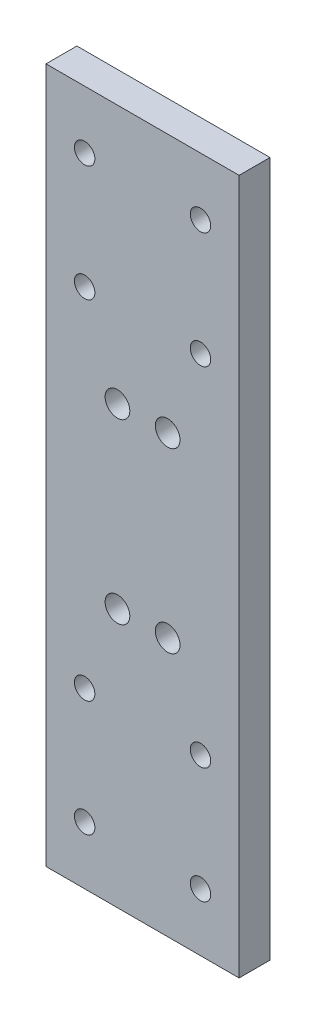
SolidWorks part; units mm, degrees
ref_plane "Front Plane" through (0, 0, 0) normal (0, 0, 1) x (1, 0, 0)
ref_plane "Top Plane" through (0, 0, 0) normal (0, 1, 0) x (1, 0, 0)
ref_plane "Right Plane" through (0, 0, 0) normal (1, 0, 0) x (0, 0, -1)
sketch "Sketch1" plane through (0, 0, 0) normal (0, 0, 1) x (1, 0, 0)
  line L0 (55, 0) -> (-55, 0) construction
  line L1 (-25, 90) -> (25, 90)
  line L2 (-25, 90) -> (-25, -90)
  line L3 (-25, -90) -> (25, -90)
  line L4 (25, 90) -> (25, -90)
  line L5 (0, -55) -> (0, 55) construction
  dimension "D1" = 50
  dimension "D2" = 180
  dimension "D3" = 90
  dimension "D4" = 25
extrude "Boss-Extrude1" add sketch "Sketch1" along normal blind 8
hole_wizard "M5 Clearance Hole1" positions "Sketch3" profile "Sketch2" hole size "M5" standard "ISO" end condition through all
sketch "Sketch3" plane through (0, 0, 8) normal (0, 0, 1) x (1, 0, 0)
  line L0 (55, 0) -> (-55, 0) construction
  line L1 (0, -55) -> (0, 55) construction
  line L2 (-74.3984, 0) -> (68.6052, 0) construction
  line L4 (0, 41.1376) -> (0, -28.8663) construction
  point P0 (-15, 45)
  point P23 (-15, -45)
  point P24 (15, -45)
  point P25 (15, 45)
  point P27 (-15, 75)
  point P31 (-15, -75)
  point P33 (15, -75)
  point P34 (15, 75)
  dimension "D1" = 45
  dimension "D2" = 15
  dimension "D3" = 15
  dimension "D4" = 30
sketch "Sketch2" plane through (-15, 45, 8) normal (1, 0, 0) x (0, -1, 0)
  line L0 (0, 0) -> (0, 8)
  line L1 (0, 8) -> (2.65, 8)
  line L2 (2.65, 8) -> (2.65, 0)
  line L5 (2.65, 0) -> (0, 0)
  line L11 (0, -6.35) -> (0, 107.95) construction
  dimension "Thru Hole Dia." = 5.3
  dimension "Thru Hole Depth" = 8
hole_wizard "M6 Clearance Hole1" positions "Sketch5" profile "Sketch4" hole size "M6" standard "ISO" end condition through all
sketch "Sketch5" plane through (0, 0, 8) normal (0, 0, 1) x (1, 0, 0)
  line L1 (55, 0) -> (-55, 0) construction
  line L2 (-63.4314, 0) -> (43.331, 0) construction
  line L3 (0, -55) -> (0, 55) construction
  line L4 (0, 43.8481) -> (0, -35.5104) construction
  point P0 (-6.5, 23)
  point P16 (-6.5, -23)
  point P26 (6.5, -23)
  point P27 (6.5, 23)
  dimension "D1" = 6.5
  dimension "D3" = 23
sketch "Sketch4" plane through (-6.5, 23, 8) normal (1, 0, 0) x (0, -1, 0)
  line L0 (0, 0) -> (0, 8)
  line L1 (0, 8) -> (3.2, 8)
  line L2 (3.2, 8) -> (3.2, 0)
  line L5 (3.2, 0) -> (0, 0)
  line L11 (0, -6.35) -> (0, 107.95) construction
  dimension "Thru Hole Dia." = 6.4
  dimension "Thru Hole Depth" = 8
